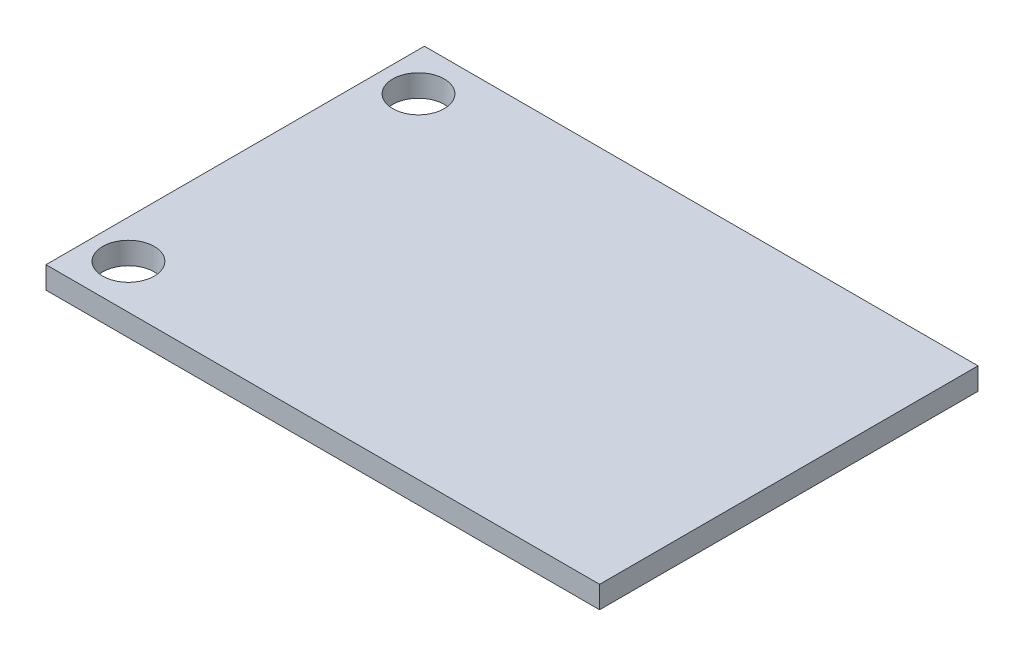
SolidWorks part; units mm, degrees
ref_plane "Front Plane" through (0, 0, 0) normal (0, 0, 1) x (1, 0, 0)
ref_plane "Top Plane" through (0, 0, 0) normal (0, 1, 0) x (1, 0, 0)
ref_plane "Right Plane" through (0, 0, 0) normal (1, 0, 0) x (0, 0, -1)
sketch "Sketch1" plane through (0, 0, 0) normal (0, 1, 0) x (1, 0, 0)
  line L1 (0, 0) -> (37.6, 0)
  line L2 (0, 0) -> (0, -25.7)
  line L3 (0, -25.7) -> (37.6, -25.7)
  line L4 (37.6, 0) -> (37.6, -25.7)
  dimension "D1" = 37.6
  dimension "D2" = 25.7
extrude "Boss-Extrude1" add sketch "Sketch1" along normal blind 1.5
sketch "Sketch2" plane through (0, 1.5, 0) normal (0, 1, 0) x (1, 0, 0)
  line L0 (0, 0) -> (0, -25.7) construction
  line L1 (37.6, 0) -> (0, 0) construction
  circle A0 centre (2.6, -3) radius 1.75
  circle A1 centre (2.6, -22.7) radius 1.75
  dimension "D1" = 3.5
  dimension "D2" = 3.5
  dimension "D3" = 2.6
  dimension "D4" = 2.6
  dimension "D5" = 19.7
  dimension "D6" = 3
extrude "Cut-Extrude1" cut sketch "Sketch2" against normal blind 1.5
equation "\"D5@Sketch2\"=16.2+3.5"
